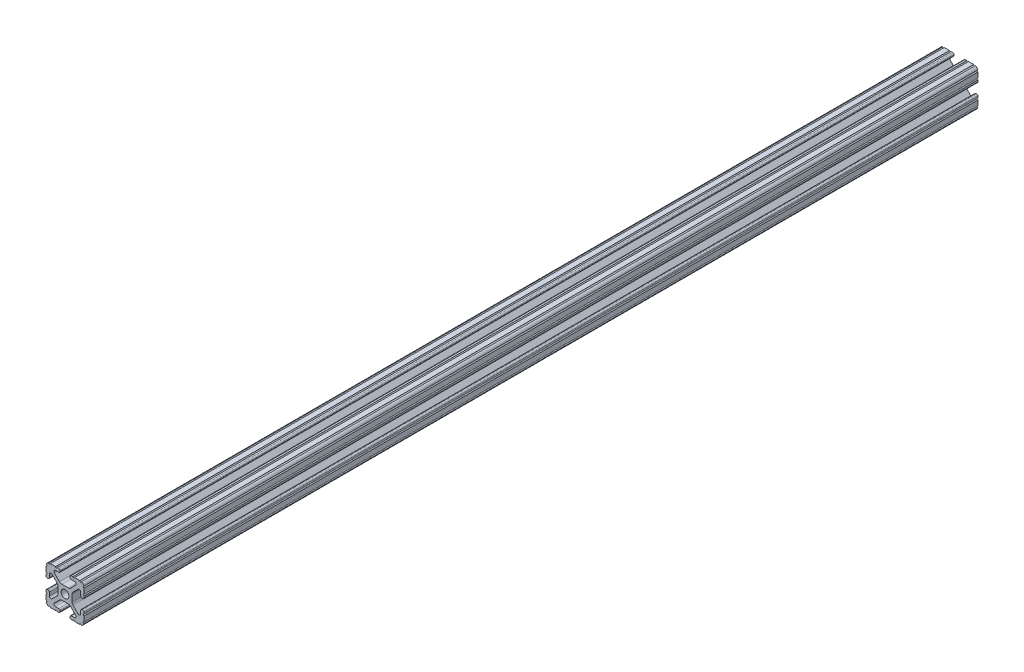
SolidWorks part; units mm, degrees
ref_plane "Front Plane" through (0, 0, 0) normal (0, 0, 1) x (1, 0, 0)
ref_plane "Top Plane" through (0, 0, 0) normal (0, 1, 0) x (1, 0, 0)
ref_plane "Right Plane" through (0, 0, 0) normal (1, 0, 0) x (0, 0, -1)
sketch "Sketch2" plane through (0, 0, 0) normal (0, 0, 1) x (1, 0, 0)
  line L0 (0, 12.7) -> (0, -12.7) construction
  line L1 (-12.7, 0) -> (12.7, 0) construction
  line L2 (3.2512, -12.7) -> (12.7, -12.7)
  line L3 (12.7, -12.7) -> (12.7, -3.2512)
  line L4 (3.2512, -12.7) -> (3.2512, -10.4902)
  line L5 (3.2512, -10.4902) -> (8.9276, -10.4902)
  line L6 (8.9276, -10.4902) -> (3.0856, -4.6482)
  line L7 (0, 0) -> (12.7, -12.7) construction
  line L8 (12.7, -3.2512) -> (10.4902, -3.2512)
  line L9 (10.4902, -3.2512) -> (10.4902, -8.9276)
  line L10 (10.4902, -8.9276) -> (4.6482, -3.0856)
  circle A0 centre (0, 0) radius 2.6035
  arc A1 (6.3485, -10.4902) -> (7.1039, -8.6665) centre (6.3485, -9.4219) ccw construction
  point P8 (0, -4.6482)
  dimension "Center Hole Diameter" = 5.207
  dimension "Rail Height" = 25.4
  dimension "Rail Width" = 25.4
  dimension "T-Slot Width" = 6.5024
  dimension "Slot Inner Width" = 14.8336
  dimension "Thickness" = 2.2098
  dimension "Slot Depth" = 5.842
  dimension "D1" = 2.2098
sketch "Sketch3" plane through (0, 0, 0) normal (1, 0, 0) x (0, 0, -1)
  line L0 (-1524, -12.7) -> (1524, -12.7) construction
  line L1 (-1498.6, 0) -> (1498.6, 0) construction
  dimension "Length" = 3048
  dimension "D1" = 25.4
sketch "Sketch4" plane through (0, 0, 0) normal (0, 0, 1) x (1, 0, 0)
  line L0 (4.1904, -12.7) -> (10.1173, -12.7)
  line L1 (3.2512, -12.7) -> (12.7, -12.7) construction
  line L2 (3.2512, -12.7) -> (3.2512, -10.4902) construction
  line L3 (3.2512, -10.4902) -> (8.9276, -10.4902) construction
  line L4 (3.2512, -11.4294) -> (3.2512, -11.7608)
  line L5 (4.1904, -10.4902) -> (6.3485, -10.4902)
  line L6 (0, -4.6482) -> (2.164, -4.6482)
  line L7 (8.9276, -10.4902) -> (3.0856, -4.6482) construction
  line L8 (3.7373, -5.2999) -> (7.1039, -8.6665)
  line L9 (12.7, -12.7) -> (12.7, -3.2512) construction
  line L10 (10.4902, -8.9276) -> (4.6482, -3.0856) construction
  line L11 (10.4902, -3.2512) -> (10.4902, -8.9276) construction
  line L12 (10.4902, -6.3485) -> (10.4902, -4.1904)
  line L13 (12.7, -3.2512) -> (10.4902, -3.2512) construction
  line L14 (11.4294, -3.2512) -> (11.7608, -3.2512)
  line L15 (12.7, -4.1904) -> (12.7, -10.1173)
  line L16 (8.6665, -7.1039) -> (5.2999, -3.7373)
  line L17 (4.6482, 0) -> (4.6482, -2.164)
  line L18 (-12.7, 0) -> (12.7, 0) construction
  line L19 (0, -4.6482) -> (0, -2.6035)
  line L20 (0, 12.7) -> (0, -12.7) construction
  line L21 (4.6482, 0) -> (2.6035, 0)
  arc A0 (3.2512, -11.7608) -> (4.1904, -12.7) centre (4.1904, -11.7608) ccw
  arc A2 (3.2512, -11.4294) -> (4.1904, -10.4902) centre (4.1904, -11.4294) cw
  arc A3 (6.3485, -10.4902) -> (7.1039, -8.6665) centre (6.3485, -9.4219) ccw
  arc A4 (2.164, -4.6482) -> (3.7373, -5.2999) centre (2.164, -6.8732) cw
  arc A5 (10.1173, -12.7) -> (12.7, -10.1173) centre (10.1173, -10.1173) ccw
  arc A6 (8.6665, -7.1039) -> (10.4902, -6.3485) centre (9.4219, -6.3485) ccw
  arc A7 (10.4902, -4.1904) -> (11.4294, -3.2512) centre (11.4294, -4.1904) cw
  arc A8 (11.7608, -3.2512) -> (12.7, -4.1904) centre (11.7608, -4.1904) cw
  arc A9 (5.2999, -3.7373) -> (4.6482, -2.164) centre (6.8732, -2.164) cw
  circle A10 centre (0, 0) radius 2.6035 construction
  arc A11 (0, -2.6035) -> (2.6035, 0) centre (0, 0) ccw
  dimension "D1" = 2.5827
  dimension "D2" = 2.225
  dimension "D3" = 0.9392
extrude "Boss-Extrude1" add sketch "Sketch4" along normal mid plane 3048
sketch "Sketch5" plane through (0, 0, 0) normal (0, 0, 1) x (1, 0, 0)
  line L0 (3.2512, -12.7) -> (12.7, -12.7) construction
  line L1 (4.1904, -10.4902) -> (6.3485, -10.4902) construction
  line L3 (0, 0) -> (12.7, -12.7) construction
  line L4 (6.3485, -10.4902) -> (6.3485, -12.7) construction
  line L5 (8.9276, -10.4902) -> (3.0856, -4.6482) construction
  circle A0 centre (10.3562, -12.7) radius 0.5524
  circle A1 centre (5.796, -12.7) radius 0.5524
  circle A2 centre (12.7, -10.3562) radius 0.5524
  circle A3 centre (12.7, -5.796) radius 0.5524
  point P10 (5.2694, -10.4902)
  point P12 (9.4219, -6.3485)
  dimension "D1" = 1.1049
extrude "Cut-Extrude1" cut sketch "Sketch5" against normal through all both and the other way through all
mirror "Mirror1" about plane through (0, 0, 0) normal (1, 0, 0) of bodies 137 134
mirror "Mirror2" about plane through (0, 0, 0) normal (0, 1, 0) of bodies 135
sketch "Sketch8" plane through (0, 0, 0) normal (0, 1, 0) x (1, 0, 0)
  line L0 (-12.58, 1524) -> (-12.58, -1524) construction
  line L1 (-25.28, 1536.7) -> (25.28, 1536.7)
  line L2 (-25.28, 1536.7) -> (-25.28, 304.8)
  line L3 (-25.28, 304.8) -> (25.28, 304.8)
  line L4 (25.28, 1536.7) -> (25.28, 304.8)
  line L5 (12.58, 1524) -> (12.58, -1524) construction
  line L6 (-6.3485, 1524) -> (-9.8037, 1524) construction
  dimension "D1" = 12.7
  dimension "D2" = 12.7
  dimension "D3" = 12.7
  dimension "D4" = 1219.2
extrude "Cut-Extrude2" cut sketch "Sketch8" against normal through all both and the other way through all
sketch "Sketch9" plane through (0, 0, 0) normal (0, 1, 0) x (1, 0, 0)
  line L0 (6.3485, -1524) -> (9.8037, -1524) construction
  line L1 (-25.4, 317.5) -> (25.28, 317.5)
  line L2 (-25.4, 317.5) -> (-25.4, -927.1)
  line L3 (-25.4, -927.1) -> (25.28, -927.1)
  line L4 (25.28, 317.5) -> (25.28, -927.1)
  line L5 (-9.8037, 304.8) -> (-6.3485, 304.8) construction
  line L7 (-12.7, 304.8) -> (-12.7, -1524) construction
  line L8 (12.58, 304.8) -> (12.58, -1524) construction
  dimension "D1" = 596.9
  dimension "D2" = 12.7
  dimension "D3" = 12.7
  dimension "D4" = 12.7
extrude "Cut-Extrude3" cut sketch "Sketch9" against normal through all both and the other way through all
equation "\"D1@Boss-Extrude1\"=\"Length@Sketch3\""
equation "\"D1@Sketch2\"=\"Thickness@Sketch2\""
equation "\"D2@Sketch4\"=\"Slot Inner Width@Sketch2\"*0.15"
equation "\"D1@Sketch4\"=\"D3@Sketch4\"*2.75"
equation "\"D3@Sketch4\"=\"Thickness@Sketch2\"*0.425"
equation "\"D1@Sketch5\"=\"Thickness@Sketch2\"*0.5"
